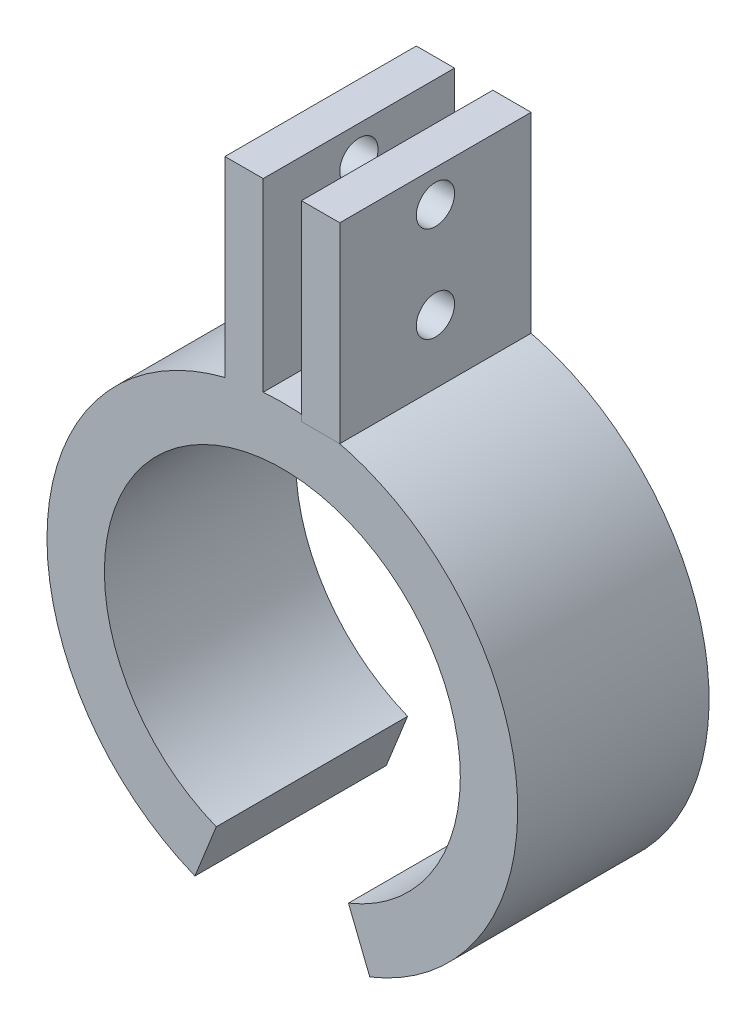
SolidWorks part; units mm, degrees
ref_plane "Front Plane" through (0, 0, 0) normal (0, 0, 1) x (1, 0, 0)
ref_plane "Top Plane" through (0, 0, 0) normal (0, 1, 0) x (1, 0, 0)
ref_plane "Right Plane" through (0, 0, 0) normal (1, 0, 0) x (0, 0, -1)
sketch "Sketch1" plane through (0, 0, 0) normal (0, 0, 1) x (1, 0, 0)
  arc A0 (3.4539, -8.6348) -> (-3.4539, -8.6348) centre (0, 0) ccw
extrude "Extrude-Thin1" add sketch "Sketch1" along normal blind 10 thin
sketch "Sketch3" plane through (0, 0, 10) normal (0, 0, 1) x (1, 0, 0)
  line L0 (-3, 11.9285) -> (-3, 21.9285)
  line L1 (4, 11.6314) -> (4, 23.1766)
  arc A0 (4.5681, -11.4203) -> (-4.5681, -11.4203) centre (0, 0) ccw construction
  point P4 (3.3518, 13.3562)
  point P8 (-1.8898, 13.64)
  point P10 (0, 0)
  dimension "D1" = 10
  dimension "D3" = 4
  dimension "D4" = 3
extrude "Extrude-Thin2" add sketch "Sketch3" against normal blind 10 thin contours L0
sketch "Sketch4" plane through (0, 0, 0) normal (0, 0, 1) x (1, 0, 0)
  line L1 (3, 11.9285) -> (3, 21.9285)
  arc A1 (4.5681, -11.4203) -> (-1, 12.2593) centre (0, 0) ccw construction
  point P0 (3.1834, 10.5293)
  point P4 (3.3518, 13.3562)
  point P8 (-1.8898, 13.64)
  point P10 (0, 0)
  dimension "D1" = 3
  dimension "D2" = 10
extrude "Extrude-Thin3" add sketch "Sketch4" along normal blind 10 separate body thin contours L1 thin type one direction reverse wall 2
sketch "Sketch5" plane through (-3, 0, 0) normal (-1, 0, 0) x (0, 0, 1)
  line L1 (10, 11.9285) -> (10, 21.9285) construction
  circle A0 centre (5, 20.2593) radius 1
  circle A1 centre (5, 15.2593) radius 1
  dimension "D3" = 5
  dimension "D1" = 3
  dimension "D2" = 5
  dimension "D4" = 5
extrude "Cut-Extrude1" cut sketch "Sketch5" against normal through all both and the other way through all
